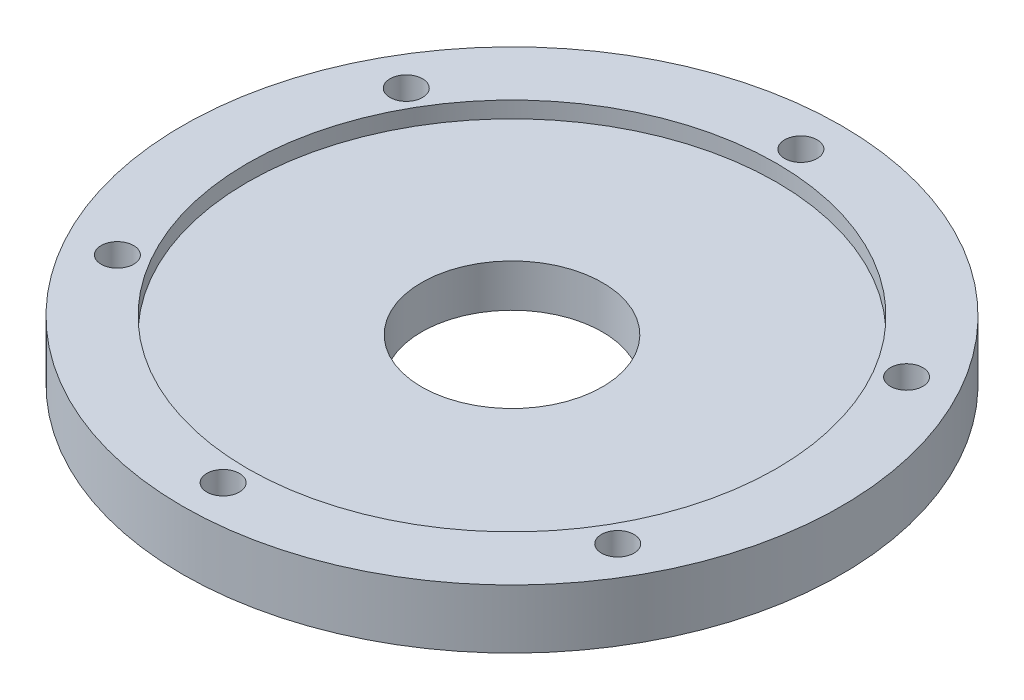
SolidWorks part; units mm, degrees
ref_plane "Front Plane" through (0, 0, 0) normal (0, 0, 1) x (1, 0, 0)
ref_plane "Top Plane" through (0, 0, 0) normal (0, 1, 0) x (1, 0, 0)
ref_plane "Right Plane" through (0, 0, 0) normal (1, 0, 0) x (0, 0, -1)
sketch "Sketch1" plane through (0, 0, 0) normal (0, 1, 0) x (1, 0, 0)
  line L0 (0, 81) -> (0, 0) construction
  line L1 (0, 0) -> (81, 0) construction
  circle A0 centre (0, 0) radius 22.225
  circle A1 centre (0, 0) radius 81
  circle A2 centre (0, 0) radius 71 construction
  circle A3 centre (0, 71) radius 4
  circle A4 centre (61.4878, 35.5) radius 4
  circle A5 centre (61.4878, -35.5) radius 4
  circle A6 centre (0, -71) radius 4
  circle A7 centre (-61.4878, -35.5) radius 4
  circle A8 centre (-61.4878, 35.5) radius 4
  point P10 (59.225, 29.8325)
  point P11 (0, 0)
  point P21 (0, 0)
  dimension "D1" = 162
  dimension "D2" = 44.45
  dimension "D3" = 142
  dimension "D4" = 8
  dimension "D5" = 6
extrude "Boss-Extrude1" add sketch "Sketch1" against normal blind 14.5
sketch "Sketch2" plane through (0, 0, 0) normal (0, 1, 0) x (1, 0, 0)
  circle A0 centre (0, 0) radius 65
  dimension "D1" = 130
extrude "Cut-Extrude1" cut sketch "Sketch2" against normal blind 4
